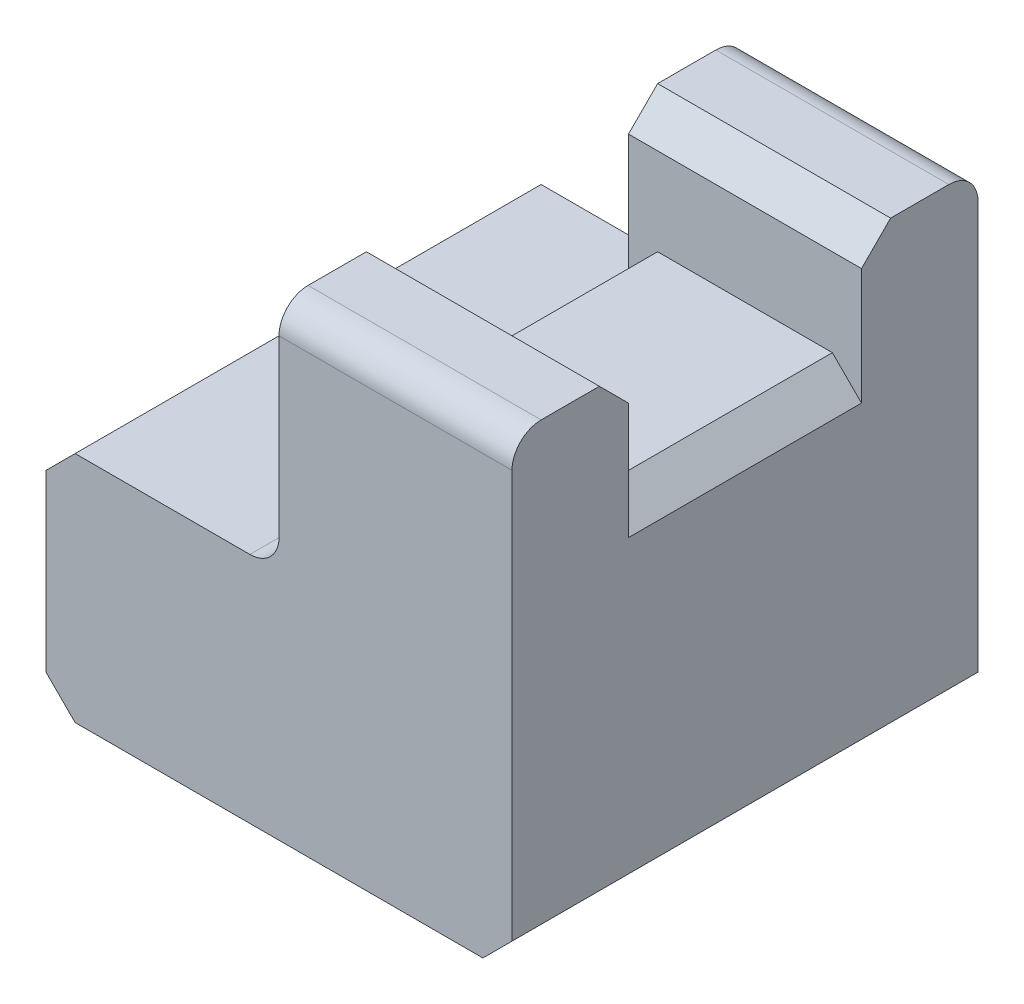
SolidWorks part; units mm, degrees
ref_plane "Front Plane" through (0, 0, 0) normal (0, 0, 1) x (1, 0, 0)
ref_plane "Top Plane" through (0, 0, 0) normal (0, 1, 0) x (1, 0, 0)
ref_plane "Right Plane" through (0, 0, 0) normal (1, 0, 0) x (0, 0, -1)
sketch "Sketch1" plane through (0, 0, 0) normal (0, 0, 1) x (1, 0, 0)
  line L0 (0, 0) -> (-80, 0)
  line L1 (-80, 0) -> (-80, 40)
  line L2 (-80, 40) -> (-40, 40)
  line L3 (-40, 40) -> (-40, 80)
  line L4 (-40, 80) -> (0, 80)
  line L5 (0, 80) -> (0, 0)
  point P3 (0, 0)
  point P8 (0, 0)
  point P9 (-2.5, 80)
  point P10 (0, 0)
  point P11 (0, 0)
  dimension "D1" = 80
  dimension "D2" = 80
  dimension "D3" = 40
  dimension "D4" = 40
extrude "Boss-Extrude1" add sketch "Sketch1" along normal blind 80
sketch "Sketch3" plane through (0, 0, 0) normal (1, 0, 0) x (0, 0, -1)
  line L0 (-60, 80) -> (-60, 60)
  line L1 (-80, 80) -> (0, 80) construction
  line L2 (-60, 60) -> (-20, 60)
  line L3 (-20, 60) -> (-20, 80)
  line L4 (-20, 80) -> (-60, 80)
  line L5 (0, 0) -> (0, 80) construction
  dimension "D1" = 40
  dimension "D2" = 20
  dimension "D3" = 20
extrude "Cut-Extrude1" cut sketch "Sketch3" against normal through all
fillet "Fillet1" radius 5 2 edges at (-20, 80, 0) (-20, 80, 80)
chamfer "Chamfer1" distance 5 angle 45 2 edges at (-20, 80, 20) (-20, 80, 60)
sketch "Sketch4" plane through (0, 40, 0) normal (0, 1, 0) x (1, 0, 0)
  line L0 (-40, -80) -> (-80, -80) construction
  line L1 (-80, -80) -> (-80, 0) construction
  circle A0 centre (-60, -40) radius 10
  dimension "D1" = 20
  dimension "D3" = 20
  dimension "D2" = 40
extrude "Cut-Extrude2" cut sketch "Sketch4" against normal through all
chamfer "Chamfer2" distance 5 angle 45 1 edges at (-80, 40, 40)
fillet "Fillet2" radius 5 1 edges at (-40, 40, 40)
chamfer "Chamfer3" distance 5 angle 45 1 edges at (-80, 0, 40)
chamfer "Chamfer4" distance 5 angle 45 1 edges at (0, 0, 40)
chamfer "Chamfer5" distance 5 angle 45 1 edges at (0, 60, 40)
chamfer "Chamfer6" distance 5 angle 45 1 edges at (-40, 60, 40)
